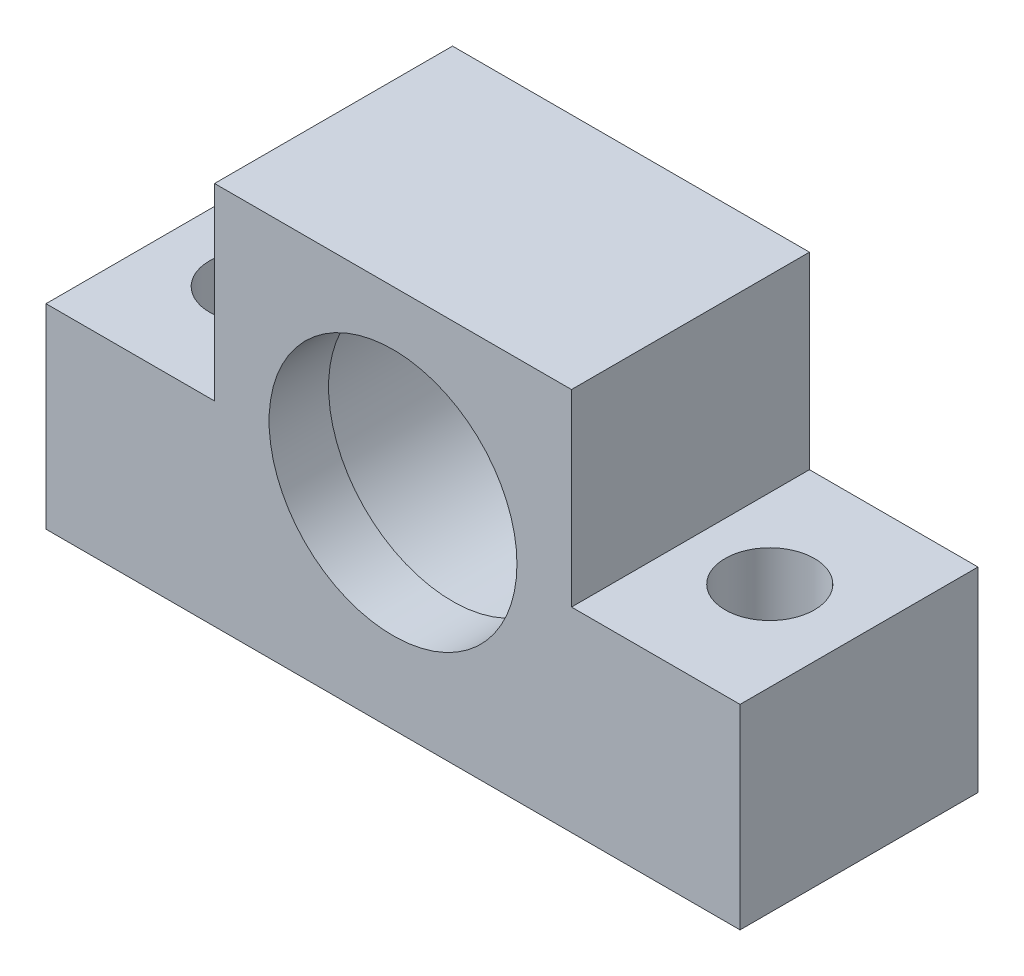
SolidWorks part; units mm, degrees
material "AISI 1045 Aço, trefilado"
ref_plane "Plano frontal" through (0, 0, 0) normal (0, 0, 1) x (1, 0, 0)
ref_plane "Plano superior" through (0, 0, 0) normal (0, 1, 0) x (1, 0, 0)
ref_plane "Plano direito" through (0, 0, 0) normal (1, 0, 0) x (0, 0, -1)
sketch "Esboço1" plane through (0, 0, 0) normal (0, 0, 1) x (1, 0, 0)
  line L0 (-35, 0) -> (35, 0)
  line L1 (35, 0) -> (35, 19.7)
  line L2 (35, 19.7) -> (18, 19.7)
  line L3 (18, 19.7) -> (18, 38.7)
  line L4 (18, 38.7) -> (-18, 38.7)
  line L5 (-18, 38.7) -> (-18, 19.7)
  line L6 (-18, 19.7) -> (-35, 19.7)
  line L7 (-35, 19.7) -> (-35, 0)
  line L8 (0, 20.7) -> (37.5306, 58.2306) construction
  circle A6 centre (0, 20.7) radius 14
  point P3 (0, 0)
  point P4 (0, 0)
  point P12 (0, 38.7)
  point P26 (0, 20.7)
  dimension "D10" = 28
  dimension "D1" = 19.7
  dimension "D2" = 38.7
  dimension "D3" = 36
  dimension "D4" = 70
  dimension "D7" = 20.7
  dimension "D8" = 45
extrude "Ressalto-extrusão3" add sketch "Esboço1" along normal blind 18
sketch "Esboço3" plane through (0, 0, 18) normal (0, 0, 1) x (1, 0, 0)
  circle A0 centre (0, 20.7) radius 12.5
  dimension "D1" = 25
extrude "Ressalto-extrusão4" add sketch "Esboço3" along normal blind 6
sketch "Esboço4" plane through (0, 19.7, 0) normal (0, 1, 0) x (1, 0, 0)
  line L0 (-18, -24) -> (-35, -24) construction
  line L4 (-35, -12) -> (35, -12) construction
  line L5 (-35, -24) -> (-35, 0) construction
  line L6 (35, -24) -> (35, 0) construction
  line L7 (0, 0) -> (0, -24) construction
  line L8 (18, -24) -> (-18, -24) construction
  circle A5 centre (-26, -12) radius 4.5
  circle A6 centre (26, -12) radius 4.5
  point P17 (0, 0)
  point P18 (-26.3471, -12)
  point P22 (0, 0)
  point P23 (26.279, -12)
  point P24 (26.3471, -12)
  point P25 (26.5514, -12)
  dimension "D1" = 9
  dimension "D2" = 12
  dimension "D3" = 52
extrude "Corte-extrusão1" cut sketch "Esboço4" against normal through all
sketch "Esboço5" plane through (0, 0, 0) normal (0, 0, -1) x (-1, 0, 0)
  line L0 (0, 20.7) -> (27.1389, 47.8389) construction
  line L1 (18, 19.7) -> (35, 19.7) construction
  circle A0 centre (0, 20.7) radius 20 construction
  dimension "D1" = 40
  dimension "D2" = 45
hole_wizard "Furo roscado de M3x0.51" positions "Esboço6" profile "Esboço8" tap size "M3x0.5" standard "Ansi Metric"
sketch "Esboço6" plane through (0, 0, 0) normal (0, 0, -1) x (-1, 0, 0)
  line L0 (0, 20.7) -> (27.1389, 47.8389) construction
  circle A0 centre (0, 20.7) radius 20 construction
  point P13 (14.1421, 34.8421)
  point P24 (14.1421, 6.5579)
  point P25 (-14.1421, 6.5579)
  point P26 (-14.1421, 34.8421)
sketch "Esboço8" plane through (-14.1421, 34.8421, 0) normal (1, 0, 0) x (0, 1, 0)
  line L0 (0, 0) -> (0, 8.2511)
  line L1 (0, 8.2511) -> (1.25, 7.5)
  line L2 (1.25, 7.5) -> (1.25, 0)
  line L5 (1.25, 0) -> (0, 0)
  line L10 (0, 8.2511) -> (-1.25, 7.5) construction
  line L11 (0, -6.35) -> (0, 107.95) construction
  dimension "Tap Drill Dia." = 2.5
  dimension "Tap Drill Depth" = 7.5
  dimension "Drill Angle" = 118
cosmetic thread "Rosca de furo1" parameters "D1"=6, "D2"=3
cosmetic thread "Rosca de furo2" parameters "D1"=6, "D2"=3
cosmetic thread "Rosca de furo3" parameters "D1"=6, "D2"=3
cosmetic thread "Rosca de furo4" parameters "D1"=6, "D2"=3
